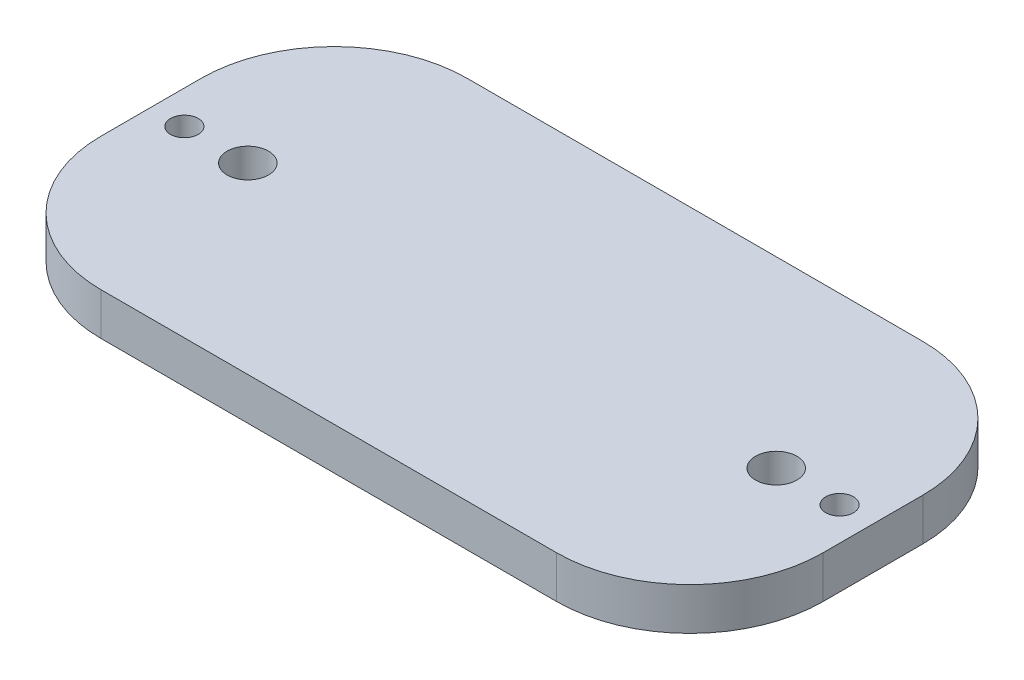
SolidWorks part; units mm, degrees
ref_plane "Front Plane" through (0, 0, 0) normal (0, 0, 1) x (1, 0, 0)
ref_plane "Top Plane" through (0, 0, 0) normal (0, 1, 0) x (1, 0, 0)
ref_plane "Right Plane" through (0, 0, 0) normal (1, 0, 0) x (0, 0, -1)
sketch "Sketch1" plane through (0, 0, 0) normal (0, 1, 0) x (1, 0, 0)
  line L0 (-49.2125, 0) -> (0, 0) construction
  line L1 (-34.2125, -27.5) -> (34.2125, -27.5)
  line L2 (-54.2125, -7.5) -> (-54.2125, 7.5)
  line L3 (-34.2125, 27.5) -> (34.2125, 27.5)
  line L4 (54.2125, -7.5) -> (54.2125, 7.5)
  line L5 (-54.2125, -27.5) -> (54.2125, 27.5) construction
  line L6 (-54.2125, 27.5) -> (54.2125, -27.5) construction
  line L7 (0, 0) -> (49.2125, 0) construction
  line L8 (-39.6875, 0) -> (0, 0) construction
  line L9 (0, 0) -> (39.6875, 0) construction
  line L10 (-32.5, 22.5) -> (-47.5, 5) construction
  line L11 (-32.5, -22.5) -> (32.5, -22.5) construction
  line L12 (-32.5, 22.5) -> (-32.5, -22.5) construction
  line L13 (-32.5, 22.5) -> (32.5, 22.5) construction
  line L14 (32.5, 22.5) -> (32.5, -22.5) construction
  line L15 (-32.5, -22.5) -> (32.5, 22.5) construction
  line L16 (-32.5, 22.5) -> (32.5, -22.5) construction
  line L17 (-47.5, 5) -> (-47.5, -5) construction
  line L18 (-32.5, 0) -> (-47.5, 0) construction
  line L19 (-47.5, -5) -> (-32.5, -22.5) construction
  line L20 (32.5, -22.5) -> (47.5, -5) construction
  line L21 (47.5, -5) -> (47.5, 5) construction
  line L22 (47.5, 5) -> (32.5, 22.5) construction
  line L23 (47.5, 0) -> (32.5, 0) construction
  circle A0 centre (-49.2125, 0) radius 2.0828
  circle A1 centre (49.2125, 0) radius 2.0828
  circle A2 centre (-39.6875, 0) radius 3.11
  circle A3 centre (39.6875, 0) radius 3.11
  arc A4 (-54.2125, 7.5) -> (-34.2125, 27.5) centre (-34.2125, 7.5) cw
  arc A5 (-34.2125, -27.5) -> (-54.2125, -7.5) centre (-34.2125, -7.5) cw
  arc A6 (54.2125, -7.5) -> (34.2125, -27.5) centre (34.2125, -7.5) cw
  arc A7 (34.2125, 27.5) -> (54.2125, 7.5) centre (34.2125, 7.5) cw
  point P0 (0, 0)
  point P31 (-47.5, 0)
  point P33 (47.5, 0)
  dimension "D2" = 6.22
  dimension "D4" = 4.1656
  dimension "D9" = 20
  dimension "D10" = 20
  dimension "D11" = 20
  dimension "D12" = 20
  dimension "D1" = 98.425
  dimension "D3" = 79.375
  dimension "D5" = 5
  dimension "D6" = 65
  dimension "D7" = 45
  dimension "D8" = 5
  dimension "D13" = 10
  dimension "D14" = 15
extrude "Boss-Extrude1" add sketch "Sketch1" along normal blind 6.35
